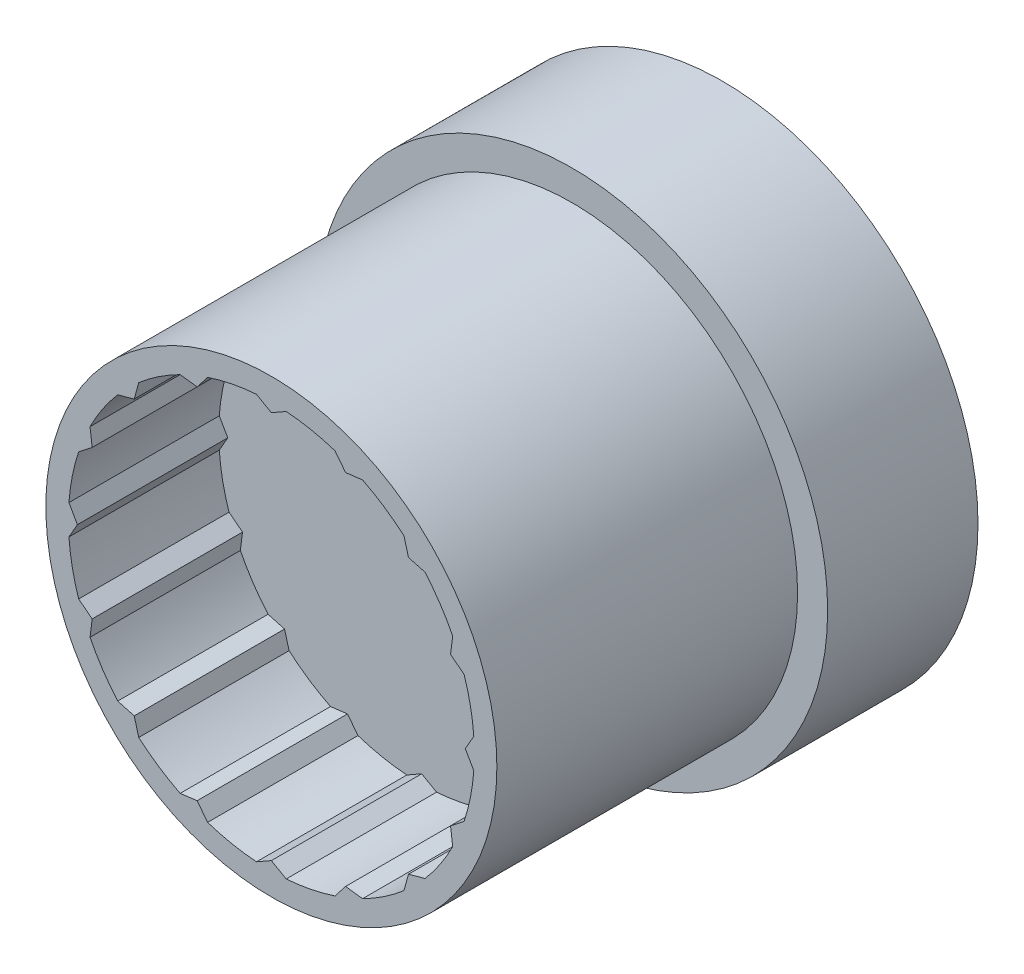
SolidWorks part; units mm, degrees
ref_plane "Front Plane" through (0, 0, 0) normal (0, 0, 1) x (1, 0, 0)
ref_plane "Top Plane" through (0, 0, 0) normal (0, 1, 0) x (1, 0, 0)
ref_plane "Right Plane" through (0, 0, 0) normal (1, 0, 0) x (0, 0, -1)
sketch "Sketch1" plane through (0, 0, 0) normal (0, 0, 1) x (1, 0, 0)
  circle A0 centre (0, 0) radius 8.5
  dimension "D1" = 17
extrude "Boss-Extrude1" add sketch "Sketch1" along normal blind 5
sketch "Sketch2" plane through (0, 0, 5) normal (0, 0, 1) x (1, 0, 0)
  circle A0 centre (0, 0) radius 7.5
  dimension "D1" = 15
extrude "Boss-Extrude2" add sketch "Sketch2" along normal blind 10
sketch "Sketch3" plane through (0, 0, 15) normal (0, 0, 1) x (1, 0, 0)
  circle A0 centre (0, 0) radius 6.75
  dimension "D1" = 13.5
extrude "Cut-Extrude1" cut sketch "Sketch3" against normal blind 5
sketch "Sketch4" plane through (0, 0, 15) normal (0, 0, 1) x (1, 0, 0)
  line L0 (-6.45, 0) -> (-6.8776, 0.75)
  line L5 (-6.8776, 0) -> (-6.45, 0) construction
  line L6 (0, 0) -> (-6.75, 0) construction
  line L7 (-6.8776, 0.75) -> (-6.8776, -0.75)
  line L8 (-6.8776, -0.75) -> (-6.45, 0)
  line L9 (-6.0671, 3.3249) -> (-6.6411, 1.939)
  line L10 (-5.959, 2.4683) -> (-6.0671, 3.3249)
  line L11 (-6.6411, 1.939) -> (-5.959, 2.4683)
  line L12 (-4.3329, 5.3936) -> (-5.3936, 4.3329)
  line L13 (-4.5608, 4.5608) -> (-4.3329, 5.3936)
  line L14 (-5.3936, 4.3329) -> (-4.5608, 4.5608)
  line L15 (-1.939, 6.6411) -> (-3.3249, 6.0671)
  line L16 (-2.4683, 5.959) -> (-1.939, 6.6411)
  line L17 (-3.3249, 6.0671) -> (-2.4683, 5.959)
  line L18 (0.75, 6.8776) -> (-0.75, 6.8776)
  line L19 (0, 6.45) -> (0.75, 6.8776)
  line L20 (-0.75, 6.8776) -> (0, 6.45)
  line L21 (3.3249, 6.0671) -> (1.939, 6.6411)
  line L22 (2.4683, 5.959) -> (3.3249, 6.0671)
  line L23 (1.939, 6.6411) -> (2.4683, 5.959)
  line L24 (5.3936, 4.3329) -> (4.3329, 5.3936)
  line L25 (4.5608, 4.5608) -> (5.3936, 4.3329)
  line L26 (4.3329, 5.3936) -> (4.5608, 4.5608)
  line L27 (6.6411, 1.939) -> (6.0671, 3.3249)
  line L28 (5.959, 2.4683) -> (6.6411, 1.939)
  line L29 (6.0671, 3.3249) -> (5.959, 2.4683)
  line L30 (6.8776, -0.75) -> (6.8776, 0.75)
  line L31 (6.45, 0) -> (6.8776, -0.75)
  line L32 (6.8776, 0.75) -> (6.45, 0)
  line L33 (6.0671, -3.3249) -> (6.6411, -1.939)
  line L34 (5.959, -2.4683) -> (6.0671, -3.3249)
  line L35 (6.6411, -1.939) -> (5.959, -2.4683)
  line L36 (4.3329, -5.3936) -> (5.3936, -4.3329)
  line L37 (4.5608, -4.5608) -> (4.3329, -5.3936)
  line L38 (5.3936, -4.3329) -> (4.5608, -4.5608)
  line L39 (1.939, -6.6411) -> (3.3249, -6.0671)
  line L40 (2.4683, -5.959) -> (1.939, -6.6411)
  line L41 (3.3249, -6.0671) -> (2.4683, -5.959)
  line L42 (-0.75, -6.8776) -> (0.75, -6.8776)
  line L43 (0, -6.45) -> (-0.75, -6.8776)
  line L44 (0.75, -6.8776) -> (0, -6.45)
  line L45 (-3.3249, -6.0671) -> (-1.939, -6.6411)
  line L46 (-2.4683, -5.959) -> (-3.3249, -6.0671)
  line L47 (-1.939, -6.6411) -> (-2.4683, -5.959)
  line L48 (-5.3936, -4.3329) -> (-4.3329, -5.3936)
  line L49 (-4.5608, -4.5608) -> (-5.3936, -4.3329)
  line L50 (-4.3329, -5.3936) -> (-4.5608, -4.5608)
  line L51 (-6.6411, -1.939) -> (-6.0671, -3.3249)
  line L52 (-5.959, -2.4683) -> (-6.6411, -1.939)
  line L53 (-6.0671, -3.3249) -> (-5.959, -2.4683)
  circle A2 centre (0, 0) radius 6.75 construction
  dimension "D1" = 1.5
  dimension "D2" = 0.3
  dimension "D3" = 16
extrude "Boss-Extrude5" add sketch "Sketch4" against normal blind 5
sketch "Sketch5" plane through (0, 0, 0) normal (0, 0, -1) x (-1, 0, 0)
  circle A0 centre (0, 0) radius 6.2708
  circle A1 centre (0, 0) radius 2.9595
extrude "Cut-Extrude2" cut sketch "Sketch5" against normal blind 1
